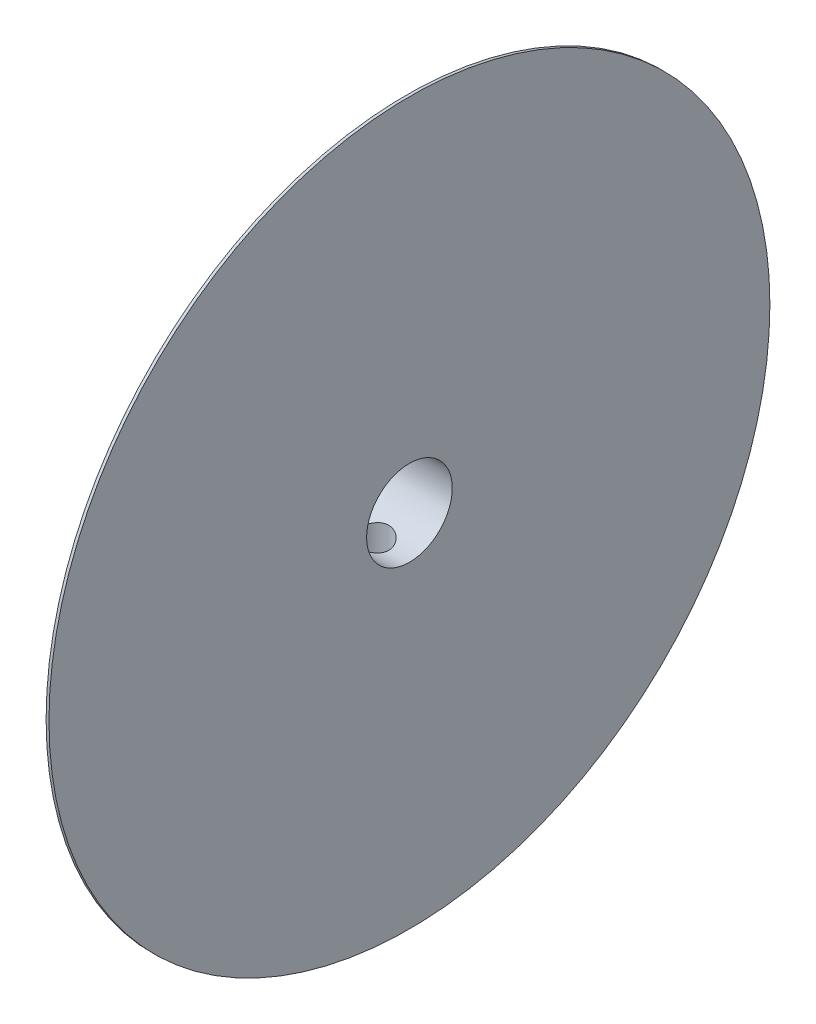
SolidWorks part; units mm, degrees
ref_plane "前视基准面" through (0, 0, 0) normal (0, 0, 1) x (1, 0, 0)
ref_plane "上视基准面" through (0, 0, 0) normal (0, 1, 0) x (1, 0, 0)
ref_plane "右视基准面" through (0, 0, 0) normal (1, 0, 0) x (0, 0, -1)
other "Configuration Table"
sketch "草图1" plane through (0, 0, 0) normal (1, 0, 0) x (0, 0, -1)
  circle A0 centre (0, 0) radius 25.25
  dimension "D1" = 50.5
extrude "凸台-拉伸1" add sketch "草图1" along normal blind 0.2
sketch "草图2" plane through (0, 0, 0) normal (-1, 0, 0) x (0, 0, 1)
  circle A0 centre (0, 0) radius 7.25
  dimension "D1" = 14.5
extrude "凸台-拉伸2" add sketch "草图2" along normal blind 5
sketch "草图3" plane through (-5, 0, 0) normal (-1, 0, 0) x (0, 0, 1)
  circle A0 centre (0, 0) radius 3
  dimension "D1" = 6
extrude "切除-拉伸1" cut sketch "草图3" against normal up to next
sketch "草图4" plane through (0, 0, 0) normal (0, 1, 0) x (1, 0, 0)
  line L0 (-5, 7.25) -> (-5, -7.25) construction
  circle A0 centre (-2.5, 0) radius 1.25
  dimension "D1" = 2.5
  dimension "D2" = 2.5
extrude "切除-拉伸2" cut sketch "草图4" against normal up to next and the other way up to next
